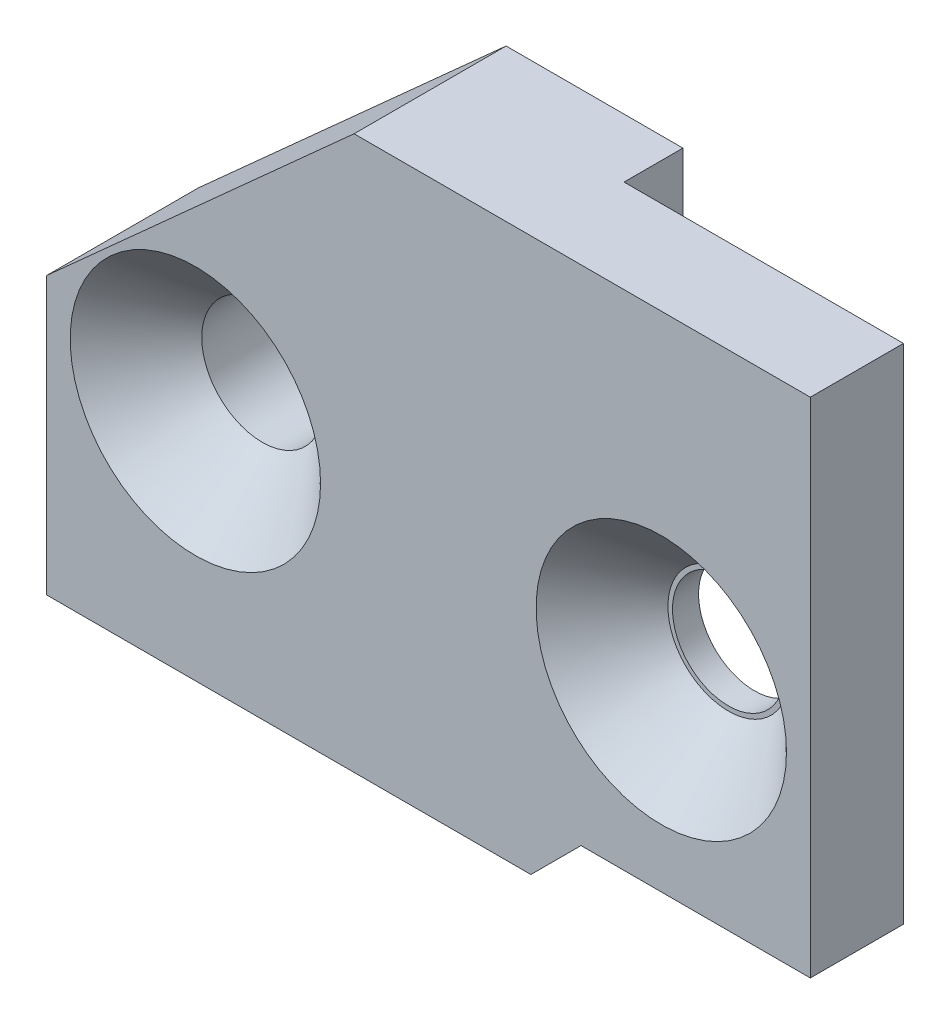
SolidWorks part; units mm, degrees
ref_plane "Alzado" through (0, 0, 0) normal (0, 0, 1) x (1, 0, 0)
ref_plane "Planta" through (0, 0, 0) normal (0, 1, 0) x (1, 0, 0)
ref_plane "Vista lateral" through (0, 0, 0) normal (1, 0, 0) x (0, 0, -1)
sketch "Croquis1" plane through (0, 0, 0) normal (0, 0, 1) x (1, 0, 0)
  line L0 (-181.7324, -74.0711) -> (-173.4777, -66.6486)
  line L1 (-173.4777, -66.6486) -> (-161.2324, -66.6486)
  line L2 (-161.2324, -66.6486) -> (-161.2324, -80.1486)
  line L3 (-161.2324, -80.1486) -> (-167.3874, -80.1486)
  line L4 (-167.3874, -80.1486) -> (-168.7324, -81.4936)
  line L5 (-168.7324, -81.4936) -> (-181.7324, -81.4936)
  line L6 (-181.7324, -81.4936) -> (-181.7324, -74.0711)
  circle A0 centre (-177.7371, -75.2236) radius 1.625
  circle A1 centre (-165.2324, -75.2236) radius 1.5
  dimension "D1" = 3.25
  dimension "D2" = 3
extrude "Saliente-Extruir1" add sketch "Croquis1" along normal blind 2.5
sketch "Croquis3" plane through (0, 0, 2.5) normal (0, 0, 1) x (1, 0, 0)
  circle A1 centre (-177.7371, -75.2236) radius 3.36
  circle A2 centre (-165.2324, -75.2236) radius 3.36
  dimension "D1" = 6.7199
extrude "Cortar-Extruir1" cut sketch "Croquis3" against normal blind 1.8 draft 44
sketch "Croquis4" plane through (0, 0, 0) normal (0, 0, -1) x (-1, 0, 0)
  line L0 (173.4777, -66.6486) -> (181.7324, -74.0711)
  line L1 (181.7324, -74.0711) -> (181.7324, -80.1486)
  line L2 (181.7324, -74.0711) -> (181.7324, -81.4936) construction
  line L3 (168.7324, -80.1486) -> (182.7324, -80.1486) construction
  line L4 (181.7324, -80.1486) -> (168.7324, -80.1486)
  line L5 (168.7324, -80.1486) -> (168.7324, -66.6486)
  line L6 (168.7324, -66.6486) -> (168.7324, -81.4936) construction
  line L7 (161.2324, -66.6486) -> (173.4777, -66.6486) construction
  line L8 (168.7324, -66.6486) -> (173.4777, -66.6486)
  circle A0 centre (177.7371, -75.2236) radius 1.625
  dimension "D1" = 3.25
extrude "Saliente-Extruir2" add sketch "Croquis4" along normal up to vertex (1.58 mm away)
